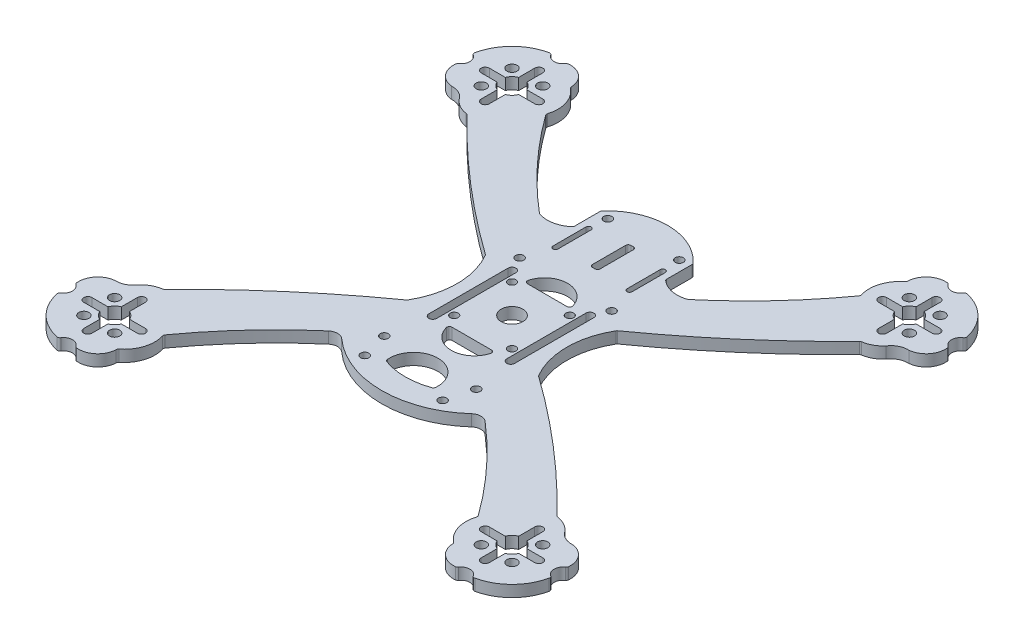
SolidWorks part; units mm, degrees
ref_plane "Front Plane" through (0, 0, 0) normal (0, 0, 1) x (1, 0, 0)
ref_plane "Top Plane" through (0, 0, 0) normal (0, 1, 0) x (1, 0, 0)
ref_plane "Right Plane" through (0, 0, 0) normal (1, 0, 0) x (0, 0, -1)
sketch "Sketch1" plane through (0, 0, 0) normal (0, 1, 0) x (1, 0, 0)
  line L0 (-18, 52.4919) -> (-18, 42.571)
  line L1 (18, 52.4919) -> (18, 42.571)
  line L2 (-13.5, 44.5) -> (-13.5, 31.5)
  line L3 (-15.5, 44.5) -> (-15.5, 31.5)
  line L4 (15.5, 44.5) -> (15.5, 31.5)
  line L5 (13.5, 44.5) -> (13.5, 31.5)
  line L6 (79.3817, 67.2817) -> (79.3817, 73.5758)
  line L7 (76.1817, 88.2817) -> (76.1817, 81.9877)
  line L8 (67.2817, 79.3817) -> (73.5758, 79.3817)
  line L9 (67.2817, 76.1817) -> (73.5758, 76.1817)
  line L10 (79.3817, 81.9877) -> (79.3817, 88.2817)
  line L11 (81.9877, 76.1817) -> (88.2817, 76.1817)
  line L12 (76.1817, 73.5758) -> (76.1817, 67.2817)
  line L13 (81.9877, 79.3817) -> (88.2817, 79.3817)
  line L14 (-79.3817, 67.2817) -> (-79.3817, 73.5758)
  line L15 (-79.3817, 81.9877) -> (-79.3817, 88.2817)
  line L16 (-76.1817, 88.2817) -> (-76.1817, 81.9877)
  line L17 (-76.1817, 73.5758) -> (-76.1817, 67.2817)
  line L18 (-67.2817, 79.3817) -> (-73.5758, 79.3817)
  line L19 (-81.9877, 79.3817) -> (-88.2817, 79.3817)
  line L20 (-67.2817, 76.1817) -> (-73.5758, 76.1817)
  line L21 (-81.9877, 76.1817) -> (-88.2817, 76.1817)
  line L22 (79.3817, -67.2817) -> (79.3817, -73.5758)
  line L23 (79.3817, -81.9877) -> (79.3817, -88.2817)
  line L24 (76.1817, -88.2817) -> (76.1817, -81.9877)
  line L25 (76.1817, -73.5758) -> (76.1817, -67.2817)
  line L26 (67.2817, -79.3817) -> (73.5758, -79.3817)
  line L27 (81.9877, -79.3817) -> (88.2817, -79.3817)
  line L28 (67.2817, -76.1817) -> (73.5758, -76.1817)
  line L29 (81.9877, -76.1817) -> (88.2817, -76.1817)
  line L30 (-79.3817, -67.2817) -> (-79.3817, -73.5758)
  line L31 (-79.3817, -81.9877) -> (-79.3817, -88.2817)
  line L32 (-76.1817, -88.2817) -> (-76.1817, -81.9877)
  line L33 (-76.1817, -73.5758) -> (-76.1817, -67.2817)
  line L34 (-67.2817, -79.3817) -> (-73.5758, -79.3817)
  line L35 (-81.9877, -79.3817) -> (-88.2817, -79.3817)
  line L36 (-67.2817, -76.1817) -> (-73.5758, -76.1817)
  line L37 (-81.9877, -76.1817) -> (-88.2817, -76.1817)
  line L38 (1.5, 46) -> (1.5, 33)
  line L39 (-1.5, 46) -> (-1.5, 33)
  line L40 (-0.5, 32) -> (0.5, 32)
  line L41 (-0.5, 47) -> (0.5, 47)
  line L42 (-13.7, 15.25) -> (-13.7, -15.75)
  line L43 (-16.8, 15.25) -> (-16.8, -15.75)
  line L44 (-7.746, -15.75) -> (7.746, -15.75)
  line L45 (13.7, 15.25) -> (13.7, -15.75)
  line L46 (16.8, 15.25) -> (16.8, -15.75)
  line L47 (-7.746, 13.75) -> (7.746, 13.75)
  circle A0 centre (0, 0) radius 4.25
  circle A1 centre (-14, 51.5) radius 1.599
  circle A2 centre (14, 51.5) radius 1.599
  arc A3 (79.3817, 73.5758) -> (81.9877, 76.1817) centre (77.7817, 77.7817) ccw
  arc A4 (-13.5, 44.5) -> (-15.5, 44.5) centre (-14.5, 44.5) ccw
  arc A5 (-15.5, 31.5) -> (-13.5, 31.5) centre (-14.5, 31.5) ccw
  arc A6 (15.5, 44.5) -> (13.5, 44.5) centre (14.5, 44.5) ccw
  arc A7 (13.5, 31.5) -> (15.5, 31.5) centre (14.5, 31.5) ccw
  arc A8 (17.7391, 53.1655) -> (-17.7391, 53.1655) centre (0, 37) ccw
  circle A9 centre (-18, -32) radius 1.6
  circle A10 centre (18, -32) radius 1.6
  arc A11 (-21.5, 0) -> (-25.6077, 15.1522) centre (-51.5, 0) ccw
  arc A12 (95.9102, 80.7393) -> (95.8218, 74.882) centre (97.7817, 77.7817) ccw
  arc A13 (74.882, 95.8218) -> (80.7393, 95.9102) centre (77.7817, 97.7817) ccw
  arc A14 (67.2817, 79.3817) -> (67.2817, 76.1817) centre (67.2817, 77.7817) ccw
  arc A15 (88.2817, 76.1817) -> (88.2817, 79.3817) centre (88.2817, 77.7817) ccw
  arc A16 (79.3817, 88.2817) -> (76.1817, 88.2817) centre (77.7817, 88.2817) ccw
  arc A17 (76.1817, 67.2817) -> (79.3817, 67.2817) centre (77.7817, 67.2817) ccw
  arc A18 (76.1817, 81.9877) -> (73.5758, 79.3817) centre (77.7817, 77.7817) ccw
  arc A19 (81.9877, 79.3817) -> (79.3817, 81.9877) centre (77.7817, 77.7817) ccw
  arc A20 (73.5758, 76.1817) -> (76.1817, 73.5758) centre (77.7817, 77.7817) ccw
  arc A21 (96.3529, 81.7956) -> (81.7956, 96.3529) centre (77.7817, 77.7817) ccw
  circle A22 centre (83.7922, 83.7922) radius 2
  circle A23 centre (71.7713, 83.7922) radius 2
  circle A24 centre (83.7922, 71.7713) radius 2
  arc A25 (18.3474, 41.8133) -> (29.0691, 39.8405) centre (25.3954, 49.9965) ccw
  arc A26 (29.0691, 39.8405) -> (61.2801, 74.4825) centre (-94.8101, 187.3229) ccw
  arc A27 (25.8895, 15.4609) -> (76.8084, 59.1751) centre (-193.1799, 322.1477) ccw
  arc A28 (65.4749, 88.3389) -> (61.4251, 75.3635) centre (72.8907, 78.9046) ccw
  arc A29 (74.1616, 96.2559) -> (65.8562, 89.0868) centre (73.3507, 88.7999) ccw
  arc A30 (89.5228, 65.8857) -> (96.2559, 74.1616) centre (88.7999, 73.3507) ccw
  arc A31 (96.2559, 74.1616) -> (95.8218, 74.882) centre (95.2618, 74.0535) ccw
  arc A32 (95.9102, 80.7393) -> (96.3529, 81.7956) centre (95.3755, 81.5844) ccw
  arc A33 (81.7956, 96.3529) -> (80.7393, 95.9102) centre (81.5844, 95.3755) ccw
  arc A34 (74.882, 95.8218) -> (74.1616, 96.2559) centre (74.0535, 95.2618) ccw
  arc A35 (65.4749, 88.3389) -> (65.8562, 89.0868) centre (64.857, 89.1251) ccw
  arc A36 (61.2801, 74.4825) -> (61.4251, 75.3635) centre (60.4697, 75.0684) ccw
  arc A37 (89.5228, 65.8857) -> (83.5687, 62.862) centre (89.1827, 59.1813) ccw
  arc A38 (77.3838, 59.4674) -> (83.5687, 62.862) centre (75.9741, 69.3676) ccw
  arc A39 (77.3838, 59.4674) -> (76.8084, 59.1751) centre (77.5247, 58.4774) ccw
  arc A40 (-81.9877, 76.1817) -> (-79.3817, 73.5758) centre (-77.7817, 77.7817) ccw
  arc A41 (-79.3817, 81.9877) -> (-81.9877, 79.3817) centre (-77.7817, 77.7817) ccw
  arc A42 (-73.5758, 79.3817) -> (-76.1817, 81.9877) centre (-77.7817, 77.7817) ccw
  arc A43 (-76.1817, 73.5758) -> (-73.5758, 76.1817) centre (-77.7817, 77.7817) ccw
  arc A44 (-81.7956, 96.3529) -> (-96.3529, 81.7956) centre (-77.7817, 77.7817) ccw
  arc A45 (-80.7393, 95.9102) -> (-81.7956, 96.3529) centre (-81.5844, 95.3755) ccw
  arc A46 (-96.3529, 81.7956) -> (-95.9102, 80.7393) centre (-95.3755, 81.5844) ccw
  arc A47 (-95.8218, 74.882) -> (-95.9102, 80.7393) centre (-97.7817, 77.7817) ccw
  arc A48 (-95.8218, 74.882) -> (-96.2559, 74.1616) centre (-95.2618, 74.0535) ccw
  arc A49 (-80.7393, 95.9102) -> (-74.882, 95.8218) centre (-77.7817, 97.7817) ccw
  arc A50 (-67.2817, 76.1817) -> (-67.2817, 79.3817) centre (-67.2817, 77.7817) ccw
  arc A51 (-88.2817, 79.3817) -> (-88.2817, 76.1817) centre (-88.2817, 77.7817) ccw
  arc A52 (-76.1817, 88.2817) -> (-79.3817, 88.2817) centre (-77.7817, 88.2817) ccw
  arc A53 (-79.3817, 67.2817) -> (-76.1817, 67.2817) centre (-77.7817, 67.2817) ccw
  circle A54 centre (-83.7922, 83.7922) radius 2
  circle A55 centre (-71.7713, 83.7922) radius 2
  circle A56 centre (-83.7922, 71.7713) radius 2
  arc A57 (-61.2801, 74.4825) -> (-29.0691, 39.8405) centre (94.8101, 187.3229) ccw
  arc A58 (-76.8084, 59.1751) -> (-25.8895, 15.4609) centre (193.1799, 322.1477) ccw
  arc A59 (-61.4251, 75.3635) -> (-65.4749, 88.3389) centre (-72.8907, 78.9046) ccw
  arc A60 (-61.4251, 75.3635) -> (-61.2801, 74.4825) centre (-60.4697, 75.0684) ccw
  arc A61 (-65.8562, 89.0868) -> (-74.1616, 96.2559) centre (-73.3507, 88.7999) ccw
  arc A62 (-65.8562, 89.0868) -> (-65.4749, 88.3389) centre (-64.857, 89.1251) ccw
  arc A63 (-74.1616, 96.2559) -> (-74.882, 95.8218) centre (-74.0535, 95.2618) ccw
  arc A64 (-96.2559, 74.1616) -> (-89.5228, 65.8857) centre (-88.7999, 73.3507) ccw
  arc A65 (-83.5687, 62.862) -> (-77.3838, 59.4674) centre (-75.9741, 69.3676) ccw
  arc A66 (-76.8084, 59.1751) -> (-77.3838, 59.4674) centre (-77.5247, 58.4774) ccw
  arc A67 (-83.5687, 62.862) -> (-89.5228, 65.8857) centre (-89.1827, 59.1813) ccw
  arc A68 (25.6077, 15.1522) -> (21.5, 0) centre (51.5, 0) ccw
  circle A69 centre (11.3137, -11.3137) radius 1.55
  circle A70 centre (11.3137, 11.3137) radius 1.55
  circle A71 centre (-11.3137, -11.3137) radius 1.55
  circle A72 centre (-11.3137, 11.3137) radius 1.55
  arc A73 (-29.0691, 39.8405) -> (-18.3474, 41.8133) centre (-25.3954, 49.9965) ccw
  arc A74 (81.9877, -76.1817) -> (79.3817, -73.5758) centre (77.7817, -77.7817) ccw
  arc A75 (79.3817, -81.9877) -> (81.9877, -79.3817) centre (77.7817, -77.7817) ccw
  arc A76 (73.5758, -79.3817) -> (76.1817, -81.9877) centre (77.7817, -77.7817) ccw
  arc A77 (76.1817, -73.5758) -> (73.5758, -76.1817) centre (77.7817, -77.7817) ccw
  arc A78 (81.7956, -96.3529) -> (96.3529, -81.7956) centre (77.7817, -77.7817) ccw
  arc A79 (80.7393, -95.9102) -> (81.7956, -96.3529) centre (81.5844, -95.3755) ccw
  arc A80 (96.3529, -81.7956) -> (95.9102, -80.7393) centre (95.3755, -81.5844) ccw
  arc A81 (95.8218, -74.882) -> (95.9102, -80.7393) centre (97.7817, -77.7817) ccw
  arc A82 (95.8218, -74.882) -> (96.2559, -74.1616) centre (95.2618, -74.0535) ccw
  arc A83 (80.7393, -95.9102) -> (74.882, -95.8218) centre (77.7817, -97.7817) ccw
  arc A84 (67.2817, -76.1817) -> (67.2817, -79.3817) centre (67.2817, -77.7817) ccw
  arc A85 (88.2817, -79.3817) -> (88.2817, -76.1817) centre (88.2817, -77.7817) ccw
  arc A86 (76.1817, -88.2817) -> (79.3817, -88.2817) centre (77.7817, -88.2817) ccw
  arc A87 (79.3817, -67.2817) -> (76.1817, -67.2817) centre (77.7817, -67.2817) ccw
  circle A88 centre (83.7922, -83.7922) radius 2
  circle A89 centre (71.7713, -83.7922) radius 2
  circle A90 centre (83.7922, -71.7713) radius 2
  arc A91 (61.2801, -74.4825) -> (30.6774, -41.2065) centre (-94.8101, -187.3229) ccw
  arc A92 (76.8084, -59.1751) -> (25.8895, -15.4609) centre (-193.1799, -322.1477) ccw
  arc A93 (61.4251, -75.3635) -> (65.4749, -88.3389) centre (72.8907, -78.9046) ccw
  arc A94 (61.4251, -75.3635) -> (61.2801, -74.4825) centre (60.4697, -75.0684) ccw
  arc A95 (65.8562, -89.0868) -> (74.1616, -96.2559) centre (73.3507, -88.7999) ccw
  arc A96 (65.8562, -89.0868) -> (65.4749, -88.3389) centre (64.857, -89.1251) ccw
  arc A97 (74.1616, -96.2559) -> (74.882, -95.8218) centre (74.0535, -95.2618) ccw
  arc A98 (96.2559, -74.1616) -> (89.5228, -65.8857) centre (88.7999, -73.3507) ccw
  arc A99 (83.5687, -62.862) -> (77.3838, -59.4674) centre (75.9741, -69.3676) ccw
  arc A100 (76.8084, -59.1751) -> (77.3838, -59.4674) centre (77.5247, -58.4774) ccw
  arc A101 (83.5687, -62.862) -> (89.5228, -65.8857) centre (89.1827, -59.1813) ccw
  arc A102 (-79.3817, -73.5758) -> (-81.9877, -76.1817) centre (-77.7817, -77.7817) ccw
  arc A103 (-81.9877, -79.3817) -> (-79.3817, -81.9877) centre (-77.7817, -77.7817) ccw
  arc A104 (-76.1817, -81.9877) -> (-73.5758, -79.3817) centre (-77.7817, -77.7817) ccw
  arc A105 (-73.5758, -76.1817) -> (-76.1817, -73.5758) centre (-77.7817, -77.7817) ccw
  arc A106 (-96.3529, -81.7956) -> (-81.7956, -96.3529) centre (-77.7817, -77.7817) ccw
  arc A107 (-81.7956, -96.3529) -> (-80.7393, -95.9102) centre (-81.5844, -95.3755) ccw
  arc A108 (-95.9102, -80.7393) -> (-96.3529, -81.7956) centre (-95.3755, -81.5844) ccw
  arc A109 (-95.9102, -80.7393) -> (-95.8218, -74.882) centre (-97.7817, -77.7817) ccw
  arc A110 (-96.2559, -74.1616) -> (-95.8218, -74.882) centre (-95.2618, -74.0535) ccw
  arc A111 (-74.882, -95.8218) -> (-80.7393, -95.9102) centre (-77.7817, -97.7817) ccw
  arc A112 (-67.2817, -79.3817) -> (-67.2817, -76.1817) centre (-67.2817, -77.7817) ccw
  arc A113 (-88.2817, -76.1817) -> (-88.2817, -79.3817) centre (-88.2817, -77.7817) ccw
  arc A114 (-79.3817, -88.2817) -> (-76.1817, -88.2817) centre (-77.7817, -88.2817) ccw
  arc A115 (-76.1817, -67.2817) -> (-79.3817, -67.2817) centre (-77.7817, -67.2817) ccw
  circle A116 centre (-83.7922, -83.7922) radius 2
  circle A117 centre (-71.7713, -83.7922) radius 2
  circle A118 centre (-83.7922, -71.7713) radius 2
  arc A119 (-30.6774, -41.2065) -> (-61.2801, -74.4825) centre (94.8101, -187.3229) ccw
  arc A120 (-25.8895, -15.4609) -> (-76.8084, -59.1751) centre (193.1799, -322.1477) ccw
  arc A121 (-65.4749, -88.3389) -> (-61.4251, -75.3635) centre (-72.8907, -78.9046) ccw
  arc A122 (-61.2801, -74.4825) -> (-61.4251, -75.3635) centre (-60.4697, -75.0684) ccw
  arc A123 (-74.1616, -96.2559) -> (-65.8562, -89.0868) centre (-73.3507, -88.7999) ccw
  arc A124 (-65.4749, -88.3389) -> (-65.8562, -89.0868) centre (-64.857, -89.1251) ccw
  arc A125 (-74.882, -95.8218) -> (-74.1616, -96.2559) centre (-74.0535, -95.2618) ccw
  arc A126 (-89.5228, -65.8857) -> (-96.2559, -74.1616) centre (-88.7999, -73.3507) ccw
  arc A127 (-77.3838, -59.4674) -> (-83.5687, -62.862) centre (-75.9741, -69.3676) ccw
  arc A128 (-77.3838, -59.4674) -> (-76.8084, -59.1751) centre (-77.5247, -58.4774) ccw
  arc A129 (-89.5228, -65.8857) -> (-83.5687, -62.862) centre (-89.1827, -59.1813) ccw
  arc A130 (-25.6077, -15.1522) -> (-21.5, 0) centre (-51.5, 0) ccw
  arc A131 (21.5, 0) -> (25.6077, -15.1522) centre (51.5, 0) ccw
  arc A132 (-25.3978, -41.2657) -> (25.3978, -41.2657) centre (0, -13) ccw
  circle A133 centre (-18, 21) radius 1.6
  circle A134 centre (18, 21) radius 1.6
  arc A135 (-25.3978, -41.2657) -> (-30.6774, -41.2065) centre (-28.0713, -44.2411) ccw
  arc A136 (30.6774, -41.2065) -> (25.3978, -41.2657) centre (28.0713, -44.2411) ccw
  arc A137 (0.5, 32) -> (1.5, 33) centre (0.5, 33) ccw
  arc A138 (-1.5, 33) -> (-0.5, 32) centre (-0.5, 33) ccw
  arc A139 (1.5, 46) -> (0.5, 47) centre (0.5, 46) ccw
  arc A140 (-0.5, 47) -> (-1.5, 46) centre (-0.5, 46) ccw
  arc A141 (-13.7, 15.25) -> (-16.8, 15.25) centre (-15.25, 15.25) ccw
  arc A142 (-16.8, -15.75) -> (-13.7, -15.75) centre (-15.25, -15.75) ccw
  arc A143 (16.8, 15.25) -> (13.7, 15.25) centre (15.25, 15.25) ccw
  arc A144 (13.7, -15.75) -> (16.8, -15.75) centre (15.25, -15.75) ccw
  arc A145 (-8.8032, -40.2143) -> (8.8032, -40.2143) centre (0, -15.75) ccw
  arc A146 (9.4604, -39.3646) -> (-9.4604, -39.3646) centre (0, -38.4982) ccw
  arc A147 (-9.4604, -39.3646) -> (-8.8032, -40.2143) centre (-8.4646, -39.2734) ccw
  arc A148 (8.8032, -40.2143) -> (9.4604, -39.3646) centre (8.4646, -39.2734) ccw
  arc A149 (-8.7142, -17) -> (8.7142, -17) centre (0, -14.75) ccw
  arc A150 (-7.746, -15.75) -> (-8.7142, -17) centre (-7.746, -16.75) ccw
  arc A151 (8.7142, -17) -> (7.746, -15.75) centre (7.746, -16.75) ccw
  arc A152 (8.7142, 15) -> (-8.7142, 15) centre (0, 12.75) ccw
  arc A153 (7.746, 13.75) -> (8.7142, 15) centre (7.746, 14.75) ccw
  arc A154 (-8.7142, 15) -> (-7.746, 13.75) centre (-7.746, 14.75) ccw
  arc A155 (25.8895, 15.4609) -> (25.6077, 15.1522) centre (26.4708, 14.6471) ccw
  arc A156 (-25.6077, 15.1522) -> (-25.8895, 15.4609) centre (-26.4708, 14.6471) ccw
  arc A157 (-25.8895, -15.4609) -> (-25.6077, -15.1522) centre (-26.4708, -14.6471) ccw
  arc A158 (25.6077, -15.1522) -> (25.8895, -15.4609) centre (26.4708, -14.6471) ccw
  arc A159 (-17.7391, 53.1655) -> (-18, 52.4919) centre (-17, 52.4919) ccw
  arc A160 (18, 52.4919) -> (17.7391, 53.1655) centre (17, 52.4919) ccw
  arc A161 (18, 42.571) -> (18.3474, 41.8133) centre (19, 42.571) ccw
  arc A162 (-18.3474, 41.8133) -> (-18, 42.571) centre (-19, 42.571) ccw
  circle A163 centre (15.25, -42.4133) radius 1.6
  circle A164 centre (-15.25, -42.4133) radius 1.6
extrude "Boss-Extrude1" add sketch "Sketch1" along normal blind 4.5
